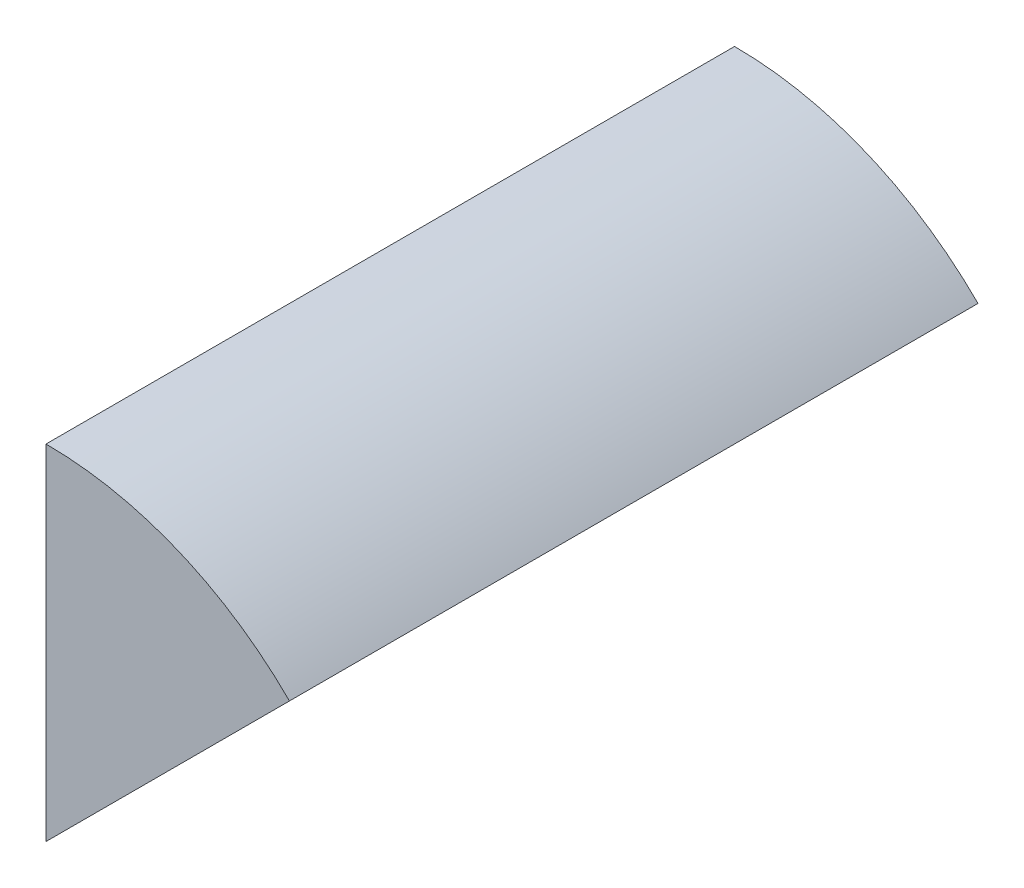
SolidWorks part; units mm, degrees
ref_plane "Alzado" through (0, 0, 0) normal (0, 0, 1) x (1, 0, 0)
ref_plane "Planta" through (0, 0, 0) normal (0, 1, 0) x (1, 0, 0)
ref_plane "Vista lateral" through (0, 0, 0) normal (1, 0, 0) x (0, 0, -1)
sketch "Croquis1" plane through (0, 0, 0) normal (0, 0, 1) x (1, 0, 0)
  line L0 (0, 25) -> (0, 0)
  line L2 (0, 0) -> (17.6777, 17.6777)
  arc A0 (17.6777, 17.6777) -> (0, 25) centre (0, 0) ccw
  dimension "D1" = 50
extrude "Saliente-Extruir1" add sketch "Croquis1" along normal blind 50
sketch "Croquis2" plane through (0, 0, 0) normal (0, 0, -1) x (-1, 0, 0)
  circle A0 centre (-6.7145, 16.3611) radius 5
  dimension "D1" = 10
extrude "Cortar-Extruir1" cut sketch "Croquis2" against normal blind 10
